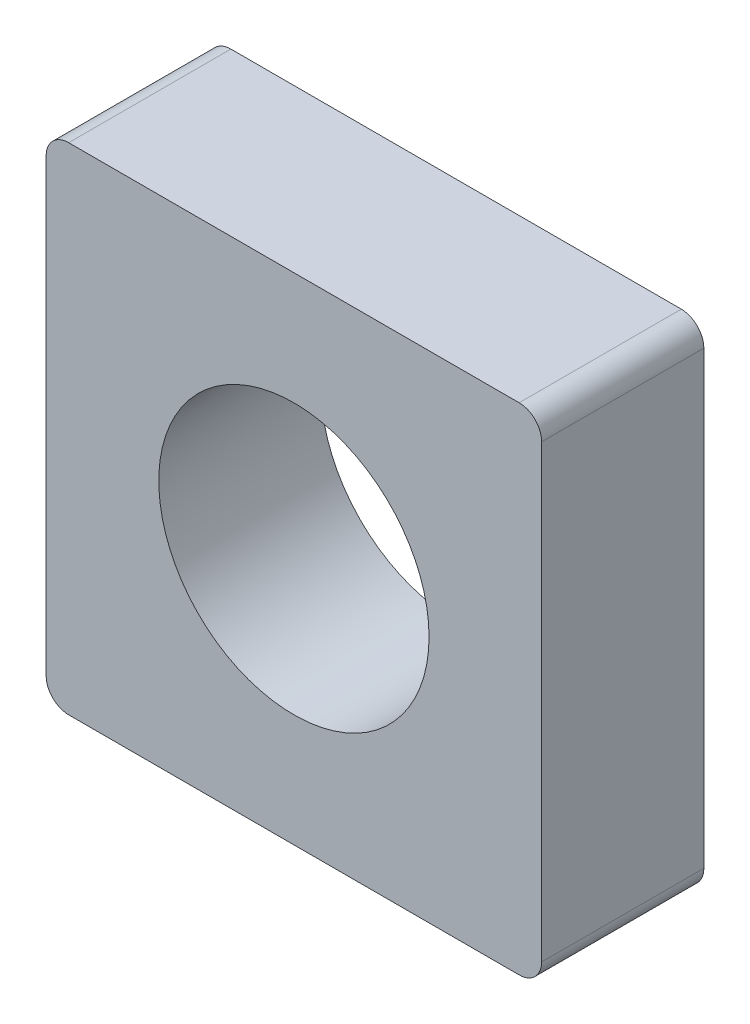
SolidWorks part; units mm, degrees
ref_plane "Front Plane" through (0, 0, 0) normal (0, 0, 1) x (1, 0, 0)
ref_plane "Top Plane" through (0, 0, 0) normal (0, 1, 0) x (1, 0, 0)
ref_plane "Right Plane" through (0, 0, 0) normal (1, 0, 0) x (0, 0, -1)
sketch "Sketch1" plane through (0, 0, 0) normal (0, 0, 1) x (1, 0, 0)
  line L1 (0.25, 0) -> (5.25, 0)
  line L2 (0, 0.25) -> (0, 5.25)
  line L3 (0.25, 5.5) -> (5.25, 5.5)
  line L4 (5.5, 0.25) -> (5.5, 5.25)
  circle A0 centre (2.75, 2.75) radius 1.5
  arc A1 (0.25, 0) -> (0, 0.25) centre (0.25, 0.25) cw
  arc A2 (5.25, 0) -> (5.5, 0.25) centre (5.25, 0.25) ccw
  arc A3 (5.25, 5.5) -> (5.5, 5.25) centre (5.25, 5.25) cw
  arc A4 (0, 5.25) -> (0.25, 5.5) centre (0.25, 5.25) cw
  point P9 (0, 0)
  point P14 (5.5, 5.5)
  point P17 (0, 5.5)
  dimension "D5" = 3
  dimension "D6" = 0.25
  dimension "D1" = 5.5
  dimension "D2" = 5.5
  dimension "D3" = 2.75
  dimension "D4" = 2.75
extrude "Boss-Extrude1" add sketch "Sketch1" along normal blind 1.8
